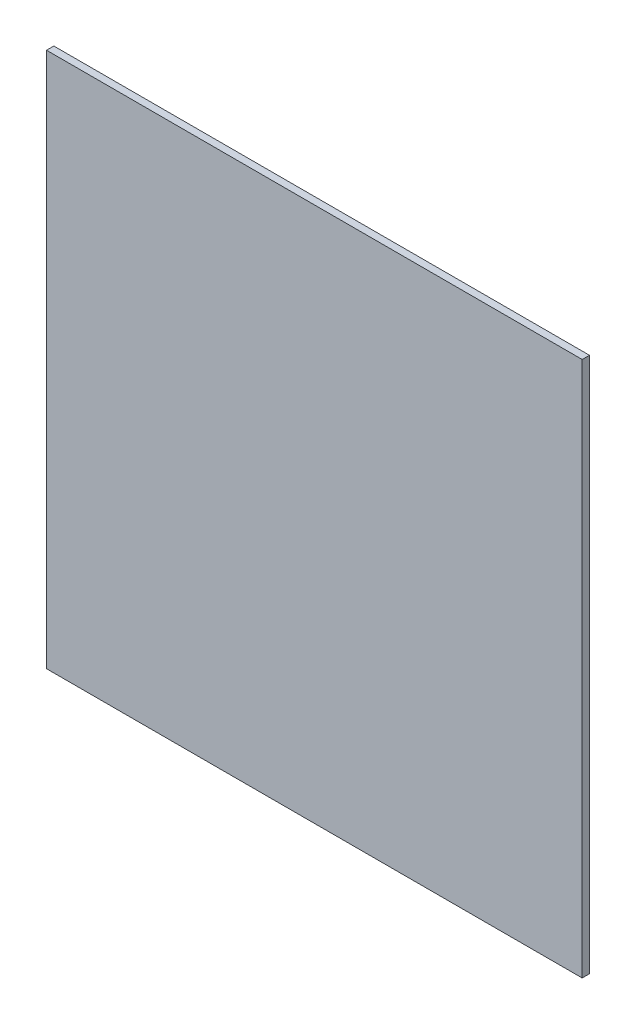
SolidWorks part; units mm, degrees
ref_plane "Спереди" through (0, 0, 0) normal (0, 0, 1) x (1, 0, 0)
ref_plane "Сверху" through (0, 0, 0) normal (0, 1, 0) x (1, 0, 0)
ref_plane "Справа" through (0, 0, 0) normal (1, 0, 0) x (0, 0, -1)
sketch "Эскиз1" plane through (0, 0, 0) normal (0, 0, 1) x (1, 0, 0)
  line L1 (-110, 110) -> (110, 110)
  line L2 (-110, 110) -> (-110, -110)
  line L3 (-110, -110) -> (110, -110)
  line L4 (110, 110) -> (110, -110)
  line L5 (-110, 110) -> (110, -110) construction
  line L6 (-110, -110) -> (110, 110) construction
  point P0 (0, 0)
  dimension "D1" = 220
  dimension "D2" = 220
extrude "Бобышка-Вытянуть1" add sketch "Эскиз1" along normal blind 3
